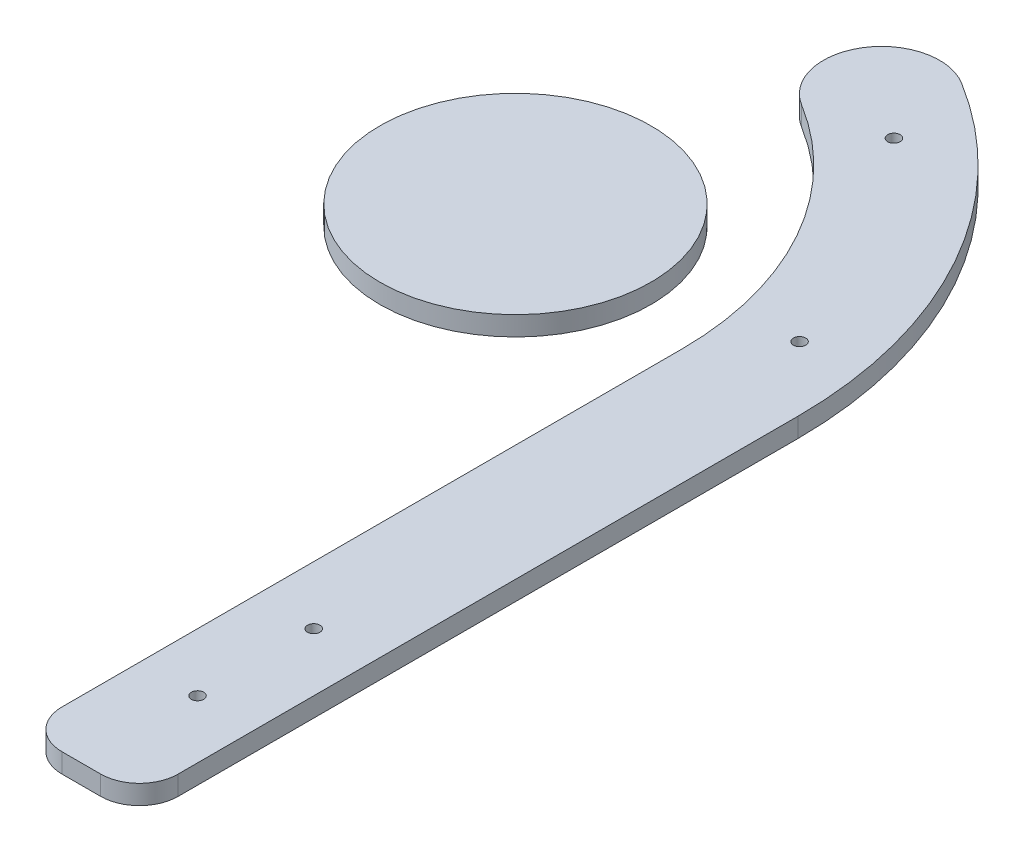
SolidWorks part; units mm, degrees
ref_plane "前基準面" through (0, 0, 0) normal (0, 0, 1) x (1, 0, 0)
ref_plane "上基準面" through (0, 0, 0) normal (0, 1, 0) x (1, 0, 0)
ref_plane "右基準面" through (0, 0, 0) normal (1, 0, 0) x (0, 0, -1)
sketch "草圖1" plane through (0, 0, 0) normal (0, 1, 0) x (1, 0, 0)
  line L0 (0, 50) -> (0, 170)
  line L1 (0, 50) -> (0, 10)
  line L2 (10, 0) -> (20, 0)
  line L3 (30, 10) -> (30, 50)
  line L4 (30, 170) -> (30, 50)
  line L5 (-23.43, 265.6526) -> (-39.1611, 240.1079) construction
  line L7 (0, 50) -> (30, 50) construction
  arc A0 (30, 170) -> (-23.43, 265.6526) centre (-82.3356, 170) ccw
  arc A1 (-23.43, 265.6526) -> (-39.1611, 240.1079) centre (-31.2956, 252.8802) ccw
  arc A2 (-39.1611, 240.1079) -> (0, 170) centre (-82.3356, 170) cw
  circle A3 centre (-53.9148, 180.9963) radius 35
  arc A4 (0, 10) -> (10, 0) centre (10, 10) ccw
  arc A5 (20, 0) -> (30, 10) centre (20, 10) ccw
  point P14 (0, 0)
  point P19 (30, 0)
  dimension "D1" = 120
  dimension "D2" = 50
  dimension "D4" = 70
  dimension "D5" = 10
  dimension "D3" = 30
extrude "伸長1" add sketch "草圖1" along normal blind 5
sketch "草圖2" plane through (0, 5, 0) normal (0, 1, 0) x (1, 0, 0)
  line L0 (15, 0) -> (15, 60) construction
  line L1 (10, 0) -> (20, 0) construction
  circle A0 centre (15, 60) radius 1.6
  circle A1 centre (15, 30) radius 1.6
  dimension "D2" = 3.2
  dimension "D3" = 3.2
  dimension "D1" = 30
extrude "伸長2" cut sketch "草圖2" against normal through all
sketch "草圖3" plane through (0, 5, 0) normal (0, 1, 0) x (1, 0, 0)
  line L0 (-44.0679, 260.7458) -> (-31.2956, 252.8802) construction
  line L1 (30, 170) -> (0, 170) construction
  arc A0 (-23.43, 265.6526) -> (-39.1611, 240.1079) centre (-31.2956, 252.8802) ccw construction
  arc A1 (-31.2956, 252.8802) -> (15, 170) centre (-82.3356, 170) cw construction
  circle A2 centre (13.5213, 186.9021) radius 1.6
  circle A3 centre (-19.7695, 244.5634) radius 1.6
  dimension "D3" = 3.2
  dimension "D1" = 50
  dimension "D2" = 10
extrude "伸長3" cut sketch "草圖3" against normal blind 10
